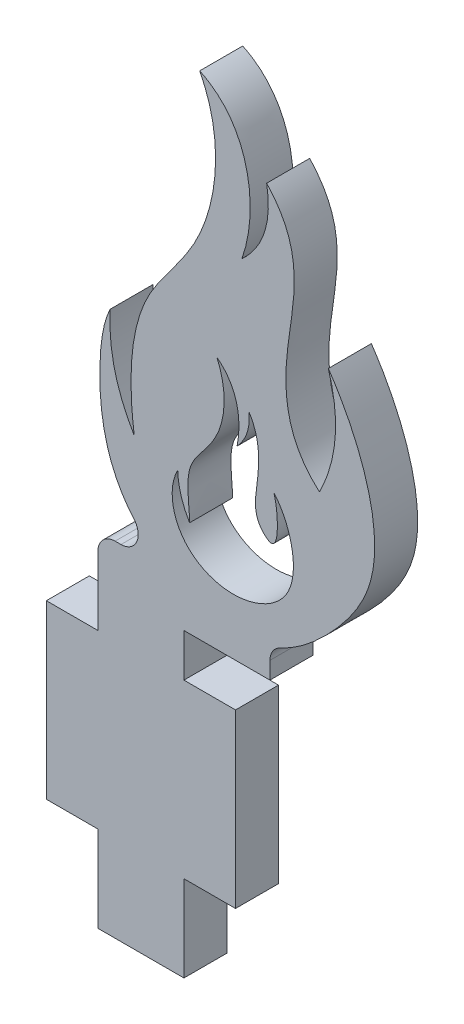
SolidWorks part; units mm, degrees
ref_plane "前视基准面" through (0, 0, 0) normal (0, 0, 1) x (1, 0, 0)
ref_plane "上视基准面" through (0, 0, 0) normal (0, 1, 0) x (1, 0, 0)
ref_plane "右视基准面" through (0, 0, 0) normal (1, 0, 0) x (0, 0, -1)
sketch "草图1" plane through (0, 0, 0) normal (0, 0, 1) x (1, 0, 0)
  line L0 (0, 10) -> (0, -10) construction
  line L1 (-2.5, 10) -> (2.5, 10)
  line L2 (-2.5, 10) -> (-2.5, -10)
  line L3 (-2.5, -10) -> (2.5, -10)
  line L4 (2.5, 10) -> (2.5, -10)
  line L5 (-2.5, 0) -> (2.5, 0) construction
  line L6 (5.5, -5) -> (2.5, -5)
  line L7 (-5.5, 5) -> (-2.5, 5)
  line L8 (-5.5, 5) -> (-5.5, -5)
  line L9 (-5.5, -5) -> (-2.5, -5)
  line L10 (-2.5, 5) -> (-2.5, -5)
  line L11 (2.5, 5) -> (2.5, -5)
  line L12 (5.5, 5) -> (2.5, 5)
  line L13 (5.5, 5) -> (5.5, -5)
  point P7 (0, -10)
  point P14 (-2.5, 0)
  dimension "D1" = 5
  dimension "D2" = 20
  dimension "D3" = 3
  dimension "D4" = 10
extrude "凸台-拉伸1" add sketch "草图1" along normal blind 2.5 contours L8 L9 L2 L7 | L4 L1 L2 L3 | L13 L12 L4 L6
sketch "草图2" plane through (0, 0, 2.5) normal (0, 0, 1) x (1, 0, 0)
  line L1 (2.5, 10) -> (7.5, 10)
  line L2 (2.5, 10) -> (2.5, 7.5)
  line L3 (2.5, 7.5) -> (7.5, 7.5)
  line L4 (7.5, 10) -> (7.5, 7.5)
  line L5 (0, 0) -> (5.5, 0) construction
  line L6 (5.5, 5) -> (5.5, -5) construction
  dimension "D1" = 7.5
  dimension "D2" = 5
extrude "凸台-拉伸3" add sketch "草图2" against normal up to surface (2.5 mm away) up to face at (0, 0, 0)
sketch "草图3" plane through (0, 0, 0) normal (0, 0, 1) x (1, 0, 0)
  line L0 (144.4774, 347.2257) -> (664.4774, 347.2257) construction
  spline S0 degree 2 poles (2.9092, 9.4629) (-2.4151, 11.4139) (-2.3827, 20.3404) (-1.7912, 21.5313) knots 0 0 0 0.735563 1 1 1
  spline S1 degree 2 poles (-1.7912, 21.5313) (-1.9602, 18.4901) (-0.3868, 15.864) knots 0 0 0 1 1 1
  spline S2 degree 3 poles (-0.3868, 15.864) (-0.7107, 18.2318) (-0.7305, 22.7063) (4.3664, 27.9311) (4.8773, 33.3575) (3.4173, 36.1404) knots 0 0 0 0 0.347 0.559931 1 1 1 1
  spline S3 degree 3 poles (3.4173, 36.1404) (6.4254, 34.7318) (6.8759, 30.6837) (5.8674, 27.9008) knots 0 0 0 0 1 1 1 1
  spline S4 degree 2 poles (5.8674, 27.9008) (7.7958, 29.6846) (7.3096, 32.4278) knots 0 0 0 1 1 1
  spline S5 degree 3 poles (7.3096, 32.4278) (9.7995, 29.7917) (7.9253, 24.9795) (8.5697, 19.9896) (10.3808, 18.4159) knots 0 0 0 0 0.581503 1 1 1 1
  spline S6 degree 2 poles (10.3808, 18.4159) (11.9462, 21.5262) (10.8968, 24.8935) knots 0 0 0 1 1 1
  spline S7 degree 3 poles (10.8968, 24.8935) (12.6497, 22.3535) (14.9469, 16.787) (10.2382, 10.2578) (6.3994, 7.8731) (2.9092, 9.4629) knots 0 0 0 0 0.442622 0.610975 1 1 1 1
  spline S8 degree 3 poles (2.1383, 15.3894) (1.5652, 14.3028) (1.9896, 11.7036) (5.5225, 10.2411) (9.7308, 12.2372) (8.6843, 15.9919) (7.714, 17.0775) knots 0 0 0 0 0.234609 0.444601 0.670183 1 1 1 1
  spline S9 degree 3 poles (7.714, 17.0775) (7.9172, 16.6763) (8.2287, 13.7135) (6.4888, 15.2617) (6.8559, 17.4795) (6.97, 19.3156) (6.2817, 20.4024) knots 0 0 0 0 0.298391 0.375085 0.606754 1 1 1 1
  spline S10 degree 2 poles (2.1383, 15.3894) (2.1814, 14.1568) (2.8289, 13.0875) knots 0 0 0 1 1 1
  spline S11 degree 3 poles (2.8289, 13.0875) (2.8282, 13.9975) (2.3939, 15.8365) (3.9477, 17.3862) (5.0142, 19.3897) (4.8891, 21.1789) (4.4146, 22.2183) knots 0 0 0 0 0.302042 0.493837 0.643329 1 1 1 1
  spline S12 degree 3 poles (4.4146, 22.2183) (5.6434, 21.2989) (5.88, 19.7033) (5.5911, 18.3307) knots 0 0 0 0 1 1 1 1
  spline S13 degree 2 poles (5.5911, 18.3307) (6.3983, 19.2003) (6.2817, 20.4024) knots 0 0 0 1 1 1
extrude "凸台-拉伸4" add sketch "草图3" along normal blind 2.5
fillet "圆角1" radius 1 3 edges at (-2.5, 10, 1.25) (1.7039, 10, 1.25) (7.5, 9.1655, 1.25)
